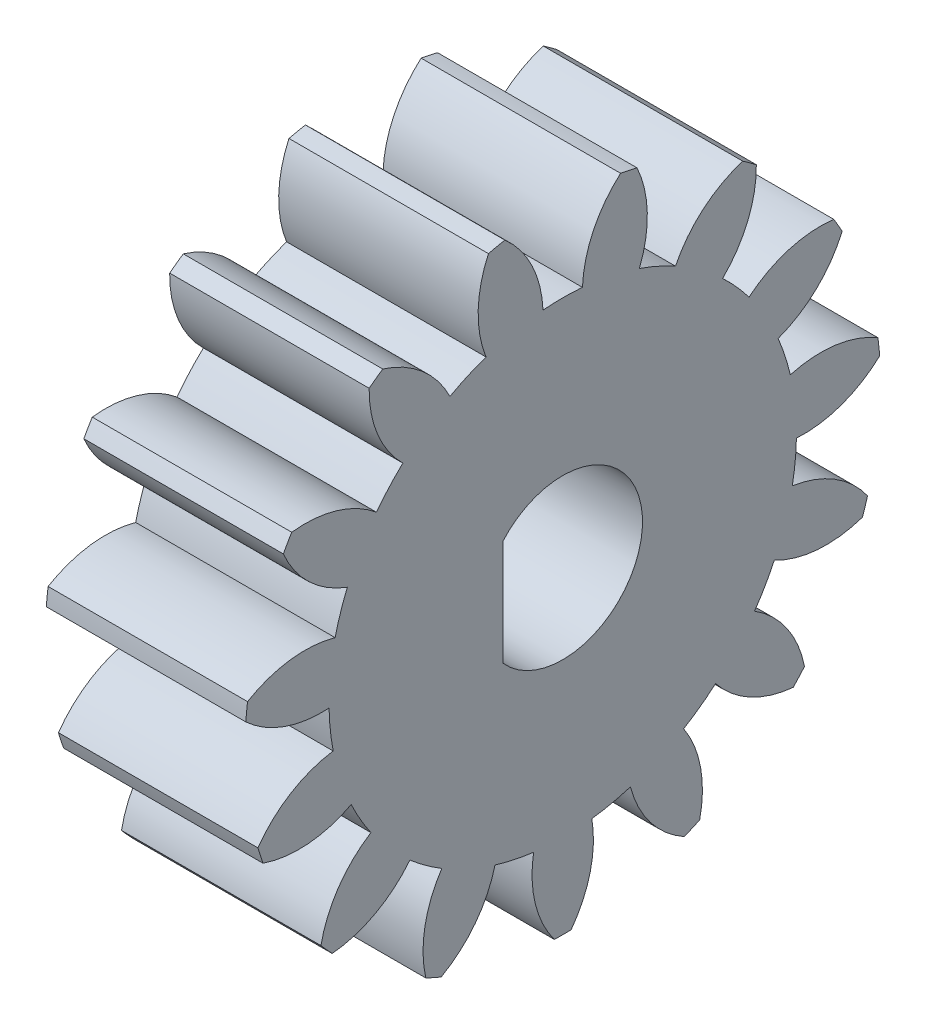
SolidWorks part; units mm, degrees
ref_plane "Plane1" through (0, 0, 0) normal (0, 0, 1) x (1, 0, 0)
ref_plane "Plane2" through (0, 0, 0) normal (0, 1, 0) x (1, 0, 0)
ref_plane "Plane3" through (0, 0, 0) normal (1, 0, 0) x (0, 0, -1)
sketch "HoldingSke" plane through (0, 0, 0) normal (0, 1, 0) x (1, 0, 0)
  line L0 (0, 0) -> (0.644, -0.1725)
  line L1 (-15, 0) -> (100, 0) construction
  line L2 (0, 0) -> (-2.1039, 2.3779)
  line L3 (0, 0) -> (-11.863, 4.5341)
  line L4 (0, 0) -> (8.3417, 2.2352)
  line L5 (0, 0) -> (-46.8476, -17.4728)
  line L6 (0, 0) -> (-6.6317, -4.4744)
  line L7 (-2.1039, 2.3779) -> (8.6586, 51.2059)
  line L8 (-76.2, 54.61) -> (-75.2, 54.61)
  line L9 (-71.009, 38.7566) -> (-53.1078, 45.2721)
  line L10 (-76.2, 71.12) -> (104.1128, 71.12)
  line L11 (0, 0) -> (-8, 0)
  line L12 (-76.2, 101.6) -> (-76.147, 101.6)
  line L13 (24.9733, 27.94) -> (52.9518, 28.4284)
  line L14 (24.9733, 27.94) -> (24.9743, 27.94)
  line L15 (24.9733, 27.94) -> (100.4006, 29.5858)
  line L16 (-63.627, -1.5) -> (-12.827, -1.5)
  circle A0 centre (0, 0) radius 3
  circle A1 centre (0, 0) radius 9.374
  circle A2 centre (0, 0) radius 37.5
  circle A3 centre (0, 0) radius 3
  dimension "MHD" = 18.748
  dimension "Hub_dia" = 75
  dimension "Bore" = 6
  dimension "MBD" = 6
  dimension "Num_teeth" = 15
  dimension "Pitch" = 0.6667
  dimension "Overall_len" = 50
  dimension "Show_teeth" = 15
  dimension "Thickness" = 8
  dimension "OAL" = 50.0001
  dimension "T_dim" = 1
  dimension "Ap" = 20
  dimension "H" = 19.05
  dimension "Pitch_radius" = 180.3128
  dimension "Width" = 8
  dimension "Backlash" = 0.053
  dimension "Addendum_fac" = 1
  dimension "Dedendum_fac" = 1.25
  dimension "Clearance_fac" = 0.25
  dimension "Dedendum_add" = 0.001
  dimension "Module" = 1.5
sketch "BasProSke" plane through (0, 0, 0) normal (0, 1, 0) x (1, 0, 0)
  line L0 (-10, 0) -> (60, 0) construction
  line L1 (0, 0) -> (0, 12.75)
  line L2 (0, 0) -> (8, 0)
  line L3 (8, 0) -> (8, 12.75)
  line L4 (8, 12.75) -> (0, 12.75)
  dimension "Thickness" = 8
  dimension "Diameter" = 25.5
revolve "Base-Revolve" add sketch "BasProSke" angle 360 about L0
sketch "TooCutSke" plane through (0, 0, 0) normal (1, 0, 0) x (0, 0, -1)
  line L1 (0, 0) -> (0, 107) construction
  line L2 (0, 0) -> (-1.2686, 11.1782) construction
  line L3 (0, 0) -> (-4.6563, 21.9061) construction
  line L4 (-1.2686, 11.1782) -> (-2.3281, 10.953) construction
  arc A0 (0.7915, 9.3405) -> (-0.7915, 9.3405) centre (0, 0) ccw
  arc A1 (2.3447, 12.5584) -> (-2.3447, 12.5584) centre (0, 0) ccw
  circle A2 centre (0, 0) radius 11.25 construction
  circle A3 centre (0, 0) radius 10.5715 construction
  arc A4 (-0.7915, 9.3405) -> (-2.3447, 12.5584) centre (-5.2877, 9.1541) ccw
  arc A5 (2.3447, 12.5584) -> (0.7915, 9.3405) centre (5.2877, 9.1541) ccw
  dimension "Root_dia" = 18.748
  dimension "Overcut_dia" = 25.5508
  dimension "Pitch_dia" = 22.5
  dimension "Base_dia" = 21.1431
  dimension "Flank_rad" = 4.5
  dimension "Half_ang" = 12
  dimension "Half_CT" = 1.0832
extrude "ToothCut" cut sketch "TooCutSke" along normal through all
fillet "Breaks" [suppressed] radius 0.03
fillet "RootFillets" [suppressed] radius 0.376
pattern_circular "TeethCuts" count 15 every 24 about axis through (-10, 0, 0) along (1, 0, 0) of "ToothCut", "RootFillets", "Breaks"
sketch "HubNeaOneSke" plane through (0, 0, 0) normal (-1, 0, 0) x (0, 0, 1)
  circle A0 centre (0, 0) radius 9.374
  dimension "Diameter" = 18.748
extrude "HubNearOne" [suppressed] add sketch "HubNeaOneSke" along normal blind 42.0001
sketch "HubNeaBotSke" plane through (0, 0, 0) normal (-1, 0, 0) x (0, 0, 1)
  circle A0 centre (0, 0) radius 9.374
  dimension "Diameter" = 18.748
extrude "HubNearBoth" [suppressed] add sketch "HubNeaBotSke" along normal blind 21
ref_plane "FarPln" through (8, 0, 0) normal (1, 0, 0) x (0, 0, -1)
sketch "HubFarSke" plane through (8, 0, 0) normal (1, 0, 0) x (0, 0, -1)
  circle A0 centre (0, 0) radius 9.374
  dimension "Diameter" = 18.748
extrude "HubFar" [suppressed] add sketch "HubFarSke" along normal blind 21
sketch "BorSke" plane through (0, 0, 0) normal (1, 0, 0) x (0, 0, -1)
  circle A0 centre (0, 0) radius 3
  dimension "Diameter" = 6
extrude "Bore" cut sketch "BorSke" along normal mid plane 100.0001
sketch "KeySke" plane through (0, 0, 0) normal (1, 0, 0) x (0, 0, -1)
  line L0 (-1, 0) -> (-1, 4)
  line L1 (-1, 4) -> (1, 4)
  line L2 (1, 4) -> (1, 0)
  line L3 (0, 0) -> (0, 34) construction
  line L4 (-1, 0) -> (1, 0)
  dimension "Offset" = 4
  dimension "Width" = 2
extrude "Keyway" [suppressed] cut sketch "KeySke" along normal mid plane 100.0001
pattern_circular "Keyway2" [suppressed] count 2 every 90 about axis through (-10, 0, 0) along (1, 0, 0)
sketch "Sketch2" plane through (0, 0, 0) normal (-1, 0, 0) x (0, 0, 1)
  circle A0 centre (0, 0) radius 3.2
  dimension "D1" = 6.4
extrude "Cut-Extrude1" cut sketch "Sketch2" against normal through all
sketch "Sketch3" plane through (0, 0, 0) normal (-1, 0, 0) x (0, 0, 1)
  line L0 (3.2, 0) -> (-0.9846, 0) construction
  line L1 (2.4, 2.1166) -> (2.4, -2.1166)
  circle A0 centre (0, 0) radius 3.2 construction
  arc A1 (2.4, -2.1166) -> (2.4, 2.1166) centre (0, 0) ccw
  dimension "D1" = 0.8
extrude "Boss-Extrude1" add sketch "Sketch3" against normal up to surface (8 mm away) up to face at (8, 0, 3.2)
equation "' \"Module@HoldingSke\" = 6.35"
equation "' \"Num_teeth@HoldingSke\" = 12"
equation "' \"Ap@HoldingSke\" =  20"
equation "' \"Ap@HoldingSke\" = 20"
equation "' \"Width@HoldingSke\" = 0.5 * 25.4"
equation "' \"Hub_dia@HoldingSke\"= 1 * 25.4"
equation "' \"Hub_dia@HoldingSke\" = 1 * 25.4"
equation "' \"Overall_len@HoldingSke\" = 1.0 * 25.4"
equation "' \"Bore@HoldingSke\" = 0.75 * 25.4"
equation "' \"T_dim@HoldingSke\" = 0.1 * 25.4"
equation "' \"Width@KeySke\" = 0.25 * 25.4"
equation "' \"Show_teeth@HoldingSke\" = 13"
equation "' \"Backlash@HoldingSke\" = 0.009 * 25.4"
equation "' \"Addendum_fac@HoldingSke\" = 1.0"
equation "' \"Dedendum_fac@HoldingSke\" = 1.25"
equation "' \"Dedendum_add@HoldingSke\" = 0.00005 * 25.4"
equation "' \"Clearance_fac@HoldingSke\" = 0.25"
equation "\"Pitch@HoldingSke\" = 1 / \"Module@HoldingSke\""
equation "\"Overcut_dia@TooCutSke\" = (\"Num_teeth@HoldingSke\" + 2 * \"Addendum_fac@HoldingSke\") / \"Pitch@HoldingSke\" + 0.002 * 25.4"
equation "\"Pitch_dia@TooCutSke\" = \"Num_teeth@HoldingSke\" / \"Pitch@HoldingSke\""
equation "\"Base_dia@TooCutSke\" = \"Num_teeth@HoldingSke\" / \"Pitch@HoldingSke\" * cos((\"Ap@HoldingSke\"  * 3.14159265 / 180))"
equation "\"Root_dia@TooCutSke\" = (\"Num_teeth@HoldingSke\" + 2) / \"Pitch@HoldingSke\" - 2 * (\"Addendum_fac@HoldingSke\" + \"Dedendum_fac@HoldingSke\") / \"Pitch@HoldingSke\" - \"Dedendum_add@HoldingSke\" * 2"
equation "\"Half_ang@TooCutSke\" = 180 / \"Num_teeth@HoldingSke\""
equation "\"Half_CT@TooCutSke\" = \"Num_teeth@HoldingSke\" / \"Pitch@HoldingSke\" * sin((3.14159265 / 2 / \"Num_teeth@HoldingSke\")) / 2 - 7 * \"Backlash@HoldingSke\" / 4"
equation "\"Flank_rad@TooCutSke\" = \"Num_teeth@HoldingSke\" / \"Pitch@HoldingSke\" / 5"
equation "\"Radius@RootFillets\" = \"Clearance_fac@HoldingSke\" / \"Pitch@HoldingSke\" + \"Dedendum_add@HoldingSke\""
equation "\"Break_rad@Breaks\" = 0.02 / \"Pitch@HoldingSke\""
equation "\"Thickness@HoldingSke\" = \"Width@HoldingSke\""
equation "\"OAL@HoldingSke\" = \"Thickness@HoldingSke\""
equation "\"MHD@HoldingSke\" = (\"Num_teeth@HoldingSke\" + 2) / \"Pitch@HoldingSke\" - 2 * (\"Addendum_fac@HoldingSke\" + \"Dedendum_fac@HoldingSke\")  / \"Pitch@HoldingSke\" - \"Dedendum_add@HoldingSke\" * 2"
equation "\"MBD@HoldingSke\" = (\"Num_teeth@HoldingSke\" + 2) / \"Pitch@HoldingSke\" - 2 * (\"Addendum_fac@HoldingSke\" + \"Dedendum_fac@HoldingSke\")  / \"Pitch@HoldingSke\" - \"Dedendum_add@HoldingSke\" * 2 - 0.002 * 25.4"
equation "\"MHD@HoldingSke\" = ((sgn( \"MHD@HoldingSke\" - \"Hub_dia@HoldingSke\" )-1)*( \"MHD@HoldingSke\" - \"Hub_dia@HoldingSke\" ))/-2+ \"Hub_dia@HoldingSke\""
equation "\"MBD@HoldingSke\" = ((sgn( \"MBD@HoldingSke\" - \"Bore@HoldingSke\" )-1)*( \"MBD@HoldingSke\" - \"Bore@HoldingSke\" ))/-2+ \"Bore@HoldingSke\""
equation "\"OAL@HoldingSke\" = ((sgn( \"OAL@HoldingSke\" - \"Overall_len@HoldingSke\" )+1)*( \"OAL@HoldingSke\" - \"Overall_len@HoldingSke\" ))/2 + \"Overall_len@HoldingSke\" + 0.000002 * 25.4"
equation "\"Num_teeth@TeethCuts\" = int( \"Show_teeth@HoldingSke\" ) + 1"
equation "\"Num_teeth@TeethCuts\" = ((sgn( \"Num_teeth@TeethCuts\" - \"Num_teeth@HoldingSke\" )-1)*( \"Num_teeth@TeethCuts\" - \"Num_teeth@HoldingSke\" ))/-2+ \"Num_teeth@HoldingSke\""
equation "\"Num_teeth@TeethCuts\" = ((sgn( \"Num_teeth@TeethCuts\" - 2.0)+1)*( \"Num_teeth@TeethCuts\" - 2.0))/2 +2.0"
equation "\"Angle@TeethCuts\" = 360.0 / \"Num_teeth@HoldingSke\""
equation "\"Diameter@BasProSke\" = (\"Num_teeth@HoldingSke\" + 2 * \"Addendum_fac@HoldingSke\") / \"Pitch@HoldingSke\""
equation "\"Thickness@BasProSke\"  = \"Thickness@HoldingSke\""
equation "' \"Fillet_rad@BasProSke\" =  \"Thickness@HoldingSke\" * 0.05"
equation "' \"Fillet_rad@BasProSke\" = \"Thickness@HoldingSke\" * 0.05"
equation "\"MHD@HoldingSke\" = ((sgn( \"MHD@HoldingSke\" - \"Root_dia@TooCutSke\" )-1)*( \"MHD@HoldingSke\" - \"Root_dia@TooCutSke\" ))/-2+ \"Root_dia@TooCutSke\""
equation "\"Diameter@HubNeaOneSke\" = \"MHD@HoldingSke\""
equation "\"Length@HubNearOne\" = \"OAL@HoldingSke\" - \"Thickness@BasProSke\""
equation "\"Diameter@HubNeaBotSke\" = \"MHD@HoldingSke\""
equation "\"Length@HubNearBoth\" = ( \"OAL@HoldingSke\" - \"Thickness@BasProSke\" ) / 2.0"
equation "\"Thickness@FarPln\" = \"Thickness@BasProSke\""
equation "\"Diameter@HubFarSke\" = \"MHD@HoldingSke\""
equation "\"Length@HubFar\" = ( \"OAL@HoldingSke\" - \"Thickness@BasProSke\" ) / 2.0"
equation "\"Diameter@BorSke\" = \"MBD@HoldingSke\""
equation "\"D1@Bore\" = \"OAL@HoldingSke\" * 2.0"
equation "\"D1@Keyway\" = \"OAL@HoldingSke\" * 2.0"
equation "\"Offset@KeySke\" = \"T_dim@HoldingSke\" + \"MBD@HoldingSke\" / 2.0"
